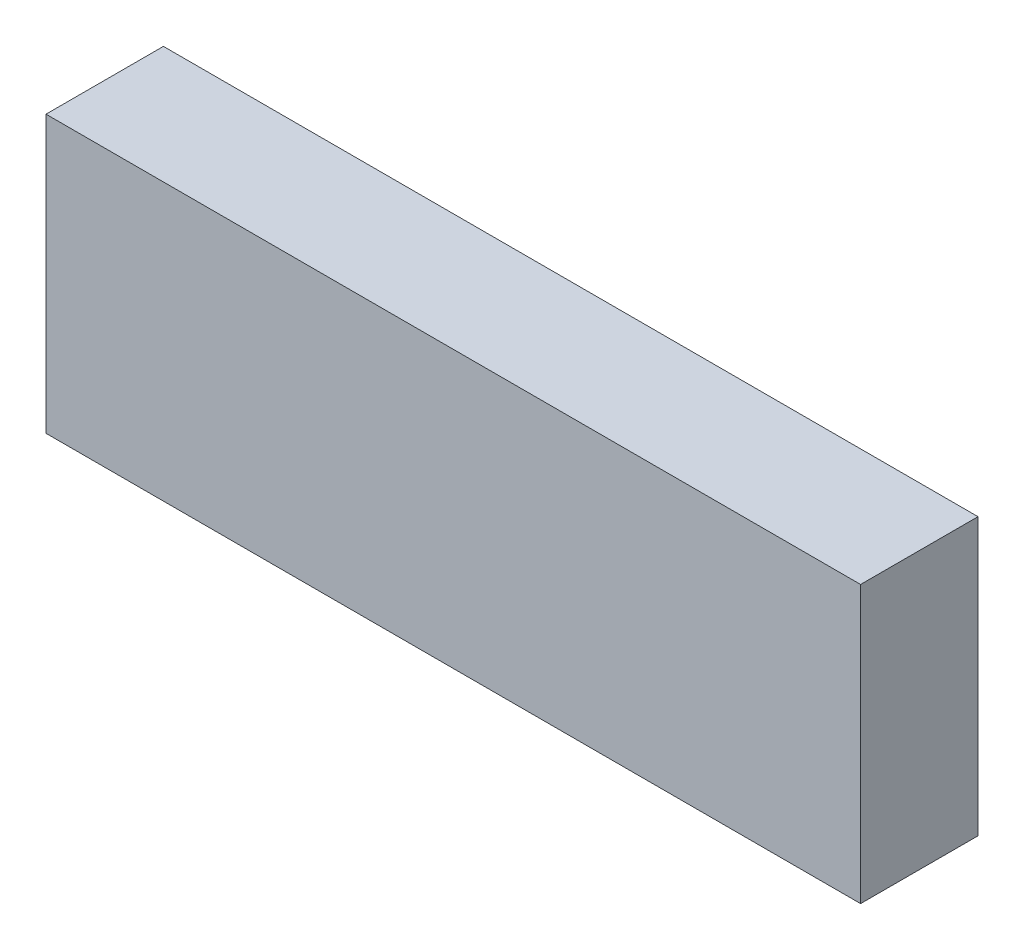
SolidWorks part; units mm, degrees
ref_plane "前视基准面" through (0, 0, 0) normal (0, 0, 1) x (1, 0, 0)
ref_plane "上视基准面" through (0, 0, 0) normal (0, 1, 0) x (1, 0, 0)
ref_plane "右视基准面" through (0, 0, 0) normal (1, 0, 0) x (0, 0, -1)
sketch "草图1" plane through (0, 0, 0) normal (0, 0, 1) x (1, 0, 0)
  line L0 (-8.325, -2.825) -> (8.325, -2.825)
  line L1 (8.325, -2.825) -> (8.325, 2.825)
  line L2 (8.325, 2.825) -> (-8.325, 2.825)
  line L3 (-8.325, 2.825) -> (-8.325, -2.825)
extrude "凸台-拉伸1" add sketch "草图1" along normal blind 2.4 from offset 0
